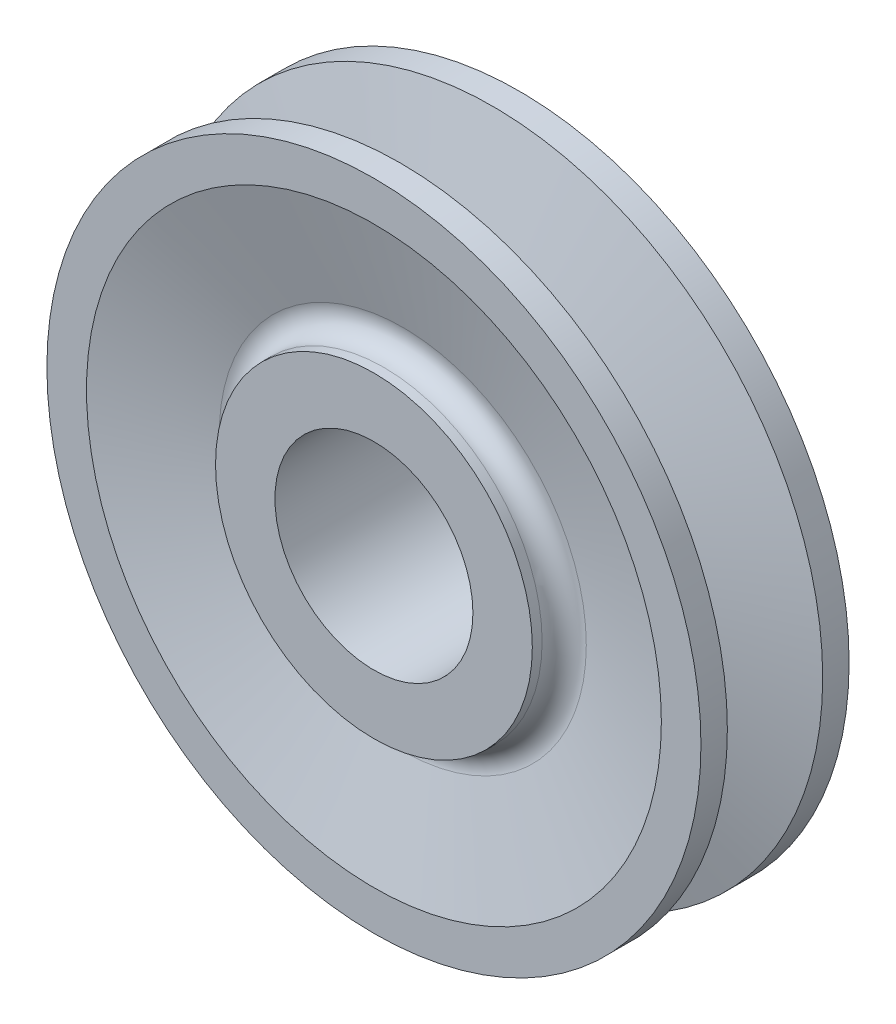
SolidWorks part; units mm, degrees
material "AISI 1020"
ref_plane "Front Plane" through (0, 0, 0) normal (0, 0, 1) x (1, 0, 0)
ref_plane "Top Plane" through (0, 0, 0) normal (0, 1, 0) x (1, 0, 0)
ref_plane "Right Plane" through (0, 0, 0) normal (1, 0, 0) x (0, 0, -1)
sketch "Sketch2" plane through (0, 0, 0) normal (1, 0, 0) x (0, 0, -1)
  line L0 (0, 9) -> (0, 46.1657) construction
  line L1 (0, 0) -> (31, 0)
  line L2 (0, 0) -> (0, 9)
  line L3 (0, 9) -> (1.4853, 9)
  line L4 (31, 0) -> (31, 9)
  line L5 (4.3758, 12.8031) -> (0, 28.5523)
  line L6 (0, 28.5523) -> (0, 34.5523)
  line L7 (0, 34.5523) -> (4, 34.5523)
  line L8 (4, 34.5523) -> (8.8768, 17)
  line L9 (8.8768, 17) -> (13.3541, 17)
  line L10 (13.3541, 17) -> (18, 35)
  line L11 (18, 35) -> (22, 35)
  line L12 (22, 35) -> (22, 29)
  line L13 (22, 29) -> (18.7735, 16.4995)
  line L14 (24.5832, 9) -> (31, 9)
  line L15 (0, -15) -> (31, -15) construction
  arc A0 (4.3758, 12.8031) -> (1.4853, 9) centre (1.4853, 12) cw
  arc A1 (18.7735, 16.4995) -> (24.5832, 9) centre (24.5832, 15) ccw
  point P23 (16.8379, 9)
  point P24 (11.1154, 17)
  dimension "D5" = 9
  dimension "D6" = 3
  dimension "D7" = 6
  dimension "D8" = 30
  dimension "D1" = 6
  dimension "D2" = 22
  dimension "D3" = 18
  dimension "D4" = 4
  dimension "D9" = 31
  dimension "D10" = 15
  dimension "D11" = 8
revolve "Revolve2" add sketch "Sketch2" angle 360 about L15
